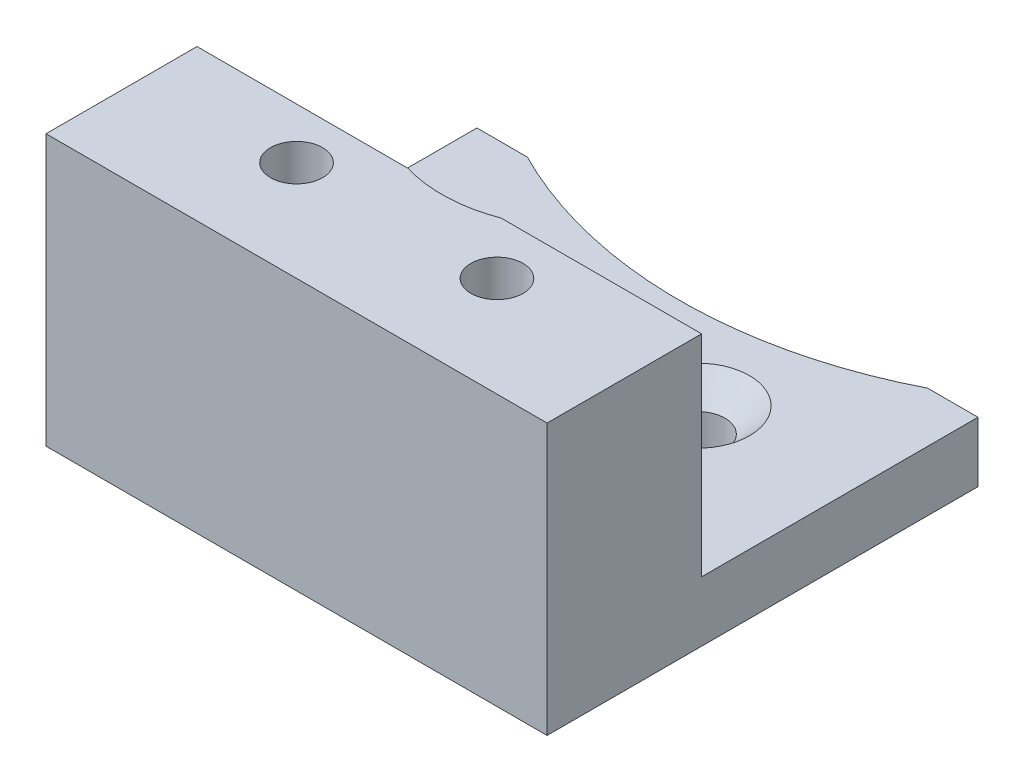
SolidWorks part; units mm, degrees
ref_plane "Front Plane" through (0, 0, 0) normal (0, 0, 1) x (1, 0, 0)
ref_plane "Top Plane" through (0, 0, 0) normal (0, 1, 0) x (1, 0, 0)
ref_plane "Right Plane" through (0, 0, 0) normal (1, 0, 0) x (0, 0, -1)
sketch "Sketch1" plane through (0, 0, 0) normal (0, 1, 0) x (1, 0, 0)
  line L0 (15, 0) -> (15, -46) construction
  line L1 (0, 0) -> (50, 0) construction
  line L2 (0, 0) -> (0, -46)
  line L3 (0, -46) -> (50, -46)
  line L4 (50, 0) -> (50, -46)
  line L5 (35, 0) -> (35, -46) construction
  line L6 (15, -16) -> (35, -16) construction
  line L7 (15, -36) -> (35, -36) construction
  line L8 (0, -3) -> (5.0312, -3)
  line L9 (44.9688, -3) -> (50, -3)
  circle A0 centre (15, -16) radius 2.6
  circle A1 centre (35, -16) radius 2.6
  circle A2 centre (35, -36) radius 2.6
  circle A3 centre (15, -36) radius 2.6
  arc A4 (5.0312, -3) -> (44.9688, -3) centre (25, 36.2077) ccw
  dimension "D5" = 5.2
  dimension "D6" = 5.2
  dimension "D7" = 5.2
  dimension "D8" = 5.2
  dimension "D11" = 44
  dimension "D1" = 15
  dimension "D2" = 15
  dimension "D3" = 10
  dimension "D4" = 20
  dimension "D9" = 50
  dimension "D10" = 46
  dimension "D12" = 3
extrude "Boss-Extrude1" add sketch "Sketch1" along normal blind 6 contours A4 L2 L3 L4 A3 A2 A1 A0
sketch "Sketch2" plane through (0, 6, 0) normal (0, 1, 0) x (1, 0, 0)
  line L1 (0, -46) -> (50, -46) construction
  circle A0 centre (25, -17.5) radius 3.25
  circle A2 centre (15, -16) radius 2.6 construction
  point P10 (25, -46)
  dimension "D1" = 6.5
  dimension "D2" = 1.5
extrude "Boss-Extrude2" add sketch "Sketch2" along normal blind 2
sketch "Sketch3" plane through (0, 8, 0) normal (0, 1, 0) x (1, 0, 0)
  circle A1 centre (25, -17.5) radius 2.5
  dimension "D1" = 5
extrude "Boss-Extrude3" add sketch "Sketch3" along normal blind 2.7
hole_wizard "CSK for M5 Flat Head Machine Screw1" positions "Sketch5" profile "Sketch6" countersink size "M5" standard "ANSI Metric" end condition through all
sketch "Sketch5" plane through (0, 6, 0) normal (0, 1, 0) x (1, 0, 0)
  point P0 (15, -16)
  point P3 (35, -16)
sketch "Sketch6" plane through (15, 6, 16) normal (1, 0, 0) x (0, 0, 1)
  line L0 (0, 0) -> (0, 6)
  line L1 (0, 6) -> (2.75, 6)
  line L2 (2.75, 6) -> (2.75, 2.45)
  line L3 (2.75, 2.45) -> (5.2, 0)
  line L5 (5.2, 0) -> (0, 0)
  line L6 (-2.75, 2.45) -> (-5.2, 0) construction
  line L11 (0, -6.35) -> (0, 107.95) construction
  dimension "Thru Hole Dia." = 5.5
  dimension "Thru Hole Depth" = 6
  dimension "Near C'Sink Dia." = 10.4
  dimension "Near C'Sink Angle" = 90
sketch "Sketch7" plane through (0, 6, 0) normal (0, 1, 0) x (1, 0, 0)
  line L0 (21.0399, -30.9283) -> (0, -30.9283)
  line L3 (0, -3) -> (0, -46) construction
  line L21 (0, -30.9283) -> (0, -46)
  line L22 (0, -46) -> (50, -46)
  line L23 (50, -46) -> (50, -30.5809)
  line L24 (50, -3) -> (50, -46) construction
  line L25 (50, -30.5809) -> (29.9891, -30.5809)
  arc A0 (21.0399, -30.9283) -> (29.9891, -30.5809) centre (25, -17.5) ccw
  circle A1 centre (15, -36) radius 5.5 construction
  circle A2 centre (15, -36) radius 2.6
  circle A3 centre (35, -36) radius 2.6
  dimension "D1" = 28
  dimension "D2" = 11
extrude "Boss-Extrude5" add sketch "Sketch7" along normal blind 21
